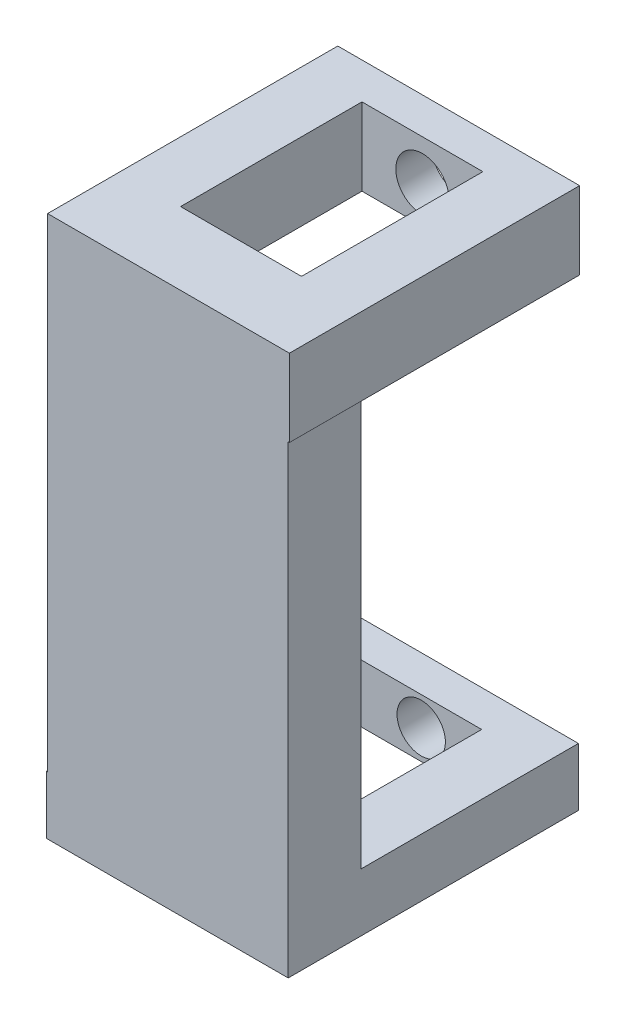
SolidWorks part; units mm, degrees
ref_plane "Płaszczyzna przednia" through (0, 0, 0) normal (0, 0, 1) x (1, 0, 0)
ref_plane "Płaszczyzna górna" through (0, 0, 0) normal (0, 1, 0) x (1, 0, 0)
ref_plane "Płaszczyzna prawa" through (0, 0, 0) normal (1, 0, 0) x (0, 0, -1)
sketch "Szkic2" plane through (0, 0, 158.8329) normal (0, 0, 1) x (1, 0, 0)
  line L0 (-31.9233, -22.4743) -> (2.0767, -22.4743) construction
  line L1 (-19.9235, -0.0745) -> (-9.9235, -0.0745)
  line L2 (-19.9235, -0.0745) -> (-19.9235, -3.2745)
  line L3 (-19.9235, -3.2745) -> (-9.9235, -3.2745)
  line L4 (-9.9235, -0.0745) -> (-9.9235, -3.2745)
  line L5 (-19.9733, -20.0743) -> (-9.9733, -20.0743)
  line L6 (-19.9733, -20.0743) -> (-19.9733, -22.4743)
  line L7 (-19.9733, -22.4743) -> (-9.9733, -22.4743)
  line L8 (-9.9733, -20.0743) -> (-9.9733, -22.4743)
  circle A0 centre (-14.9733, -21.2743) radius 1 construction
  circle A1 centre (-14.9235, -1.7745) radius 1.1 construction
  circle A2 centre (-14.9733, -21.2743) radius 1
  circle A3 centre (-14.9235, -1.7745) radius 1.1
  dimension "D1" = 10
  dimension "D2" = 5
  dimension "D3" = 1.2
  dimension "D4" = 10
  dimension "D5" = 5
  dimension "D6" = 1.7
  dimension "D7" = 1.5
extrude "Dodanie-wyciągnięcie1" add sketch "Szkic2" along normal blind 12
sketch "Szkic3" plane through (0, 0, 170.8329) normal (0, 0, 1) x (1, 0, 0)
  line L0 (-9.9235, -0.0745) -> (-19.9235, -0.0745) construction
  line L1 (-12.4235, -0.0745) -> (-17.4235, -0.0745)
  line L2 (-12.4235, -0.0745) -> (-12.4235, -3.2745)
  line L3 (-12.4235, -3.2745) -> (-17.4235, -3.2745)
  line L4 (-17.4235, -0.0745) -> (-17.4235, -3.2745)
  line L5 (-19.9235, -3.2745) -> (-9.9235, -3.2745) construction
  line L6 (-9.9733, -20.0743) -> (-19.9733, -20.0743) construction
  line L7 (-12.4733, -20.0743) -> (-17.4733, -20.0743)
  line L8 (-12.4733, -20.0743) -> (-12.4733, -22.4743)
  line L9 (-12.4733, -22.4743) -> (-17.4733, -22.4743)
  line L10 (-17.4733, -20.0743) -> (-17.4733, -22.4743)
  line L11 (-19.9733, -22.4743) -> (-9.9733, -22.4743) construction
  line L12 (-9.9733, -22.4743) -> (-9.9733, -20.0743) construction
  line L13 (-19.9733, -20.0743) -> (-19.9733, -22.4743) construction
  line L14 (-19.9235, -0.0745) -> (-19.9235, -3.2745) construction
  line L15 (-9.9235, -3.2745) -> (-9.9235, -0.0745) construction
  point P22 (-19.9235, -1.6745)
  dimension "D1" = 2.5
  dimension "D2" = 2.5
  dimension "D3" = 2.5
  dimension "D4" = 2.5
extrude "Wytnij-wyciągnięcie1" cut sketch "Szkic3" against normal blind 10.5
sketch "Szkic4" plane through (0, 0, 170.8329) normal (0, 0, 1) x (1, 0, 0)
  line L1 (-19.9235, -0.0745) -> (-9.9733, -0.0745)
  line L2 (-19.9235, -0.0745) -> (-19.9235, -22.4743)
  line L3 (-19.9235, -22.4743) -> (-9.9733, -22.4743)
  line L4 (-9.9733, -0.0745) -> (-9.9733, -22.4743)
extrude "Dodanie-wyciągnięcie2" add sketch "Szkic4" against normal blind 3
